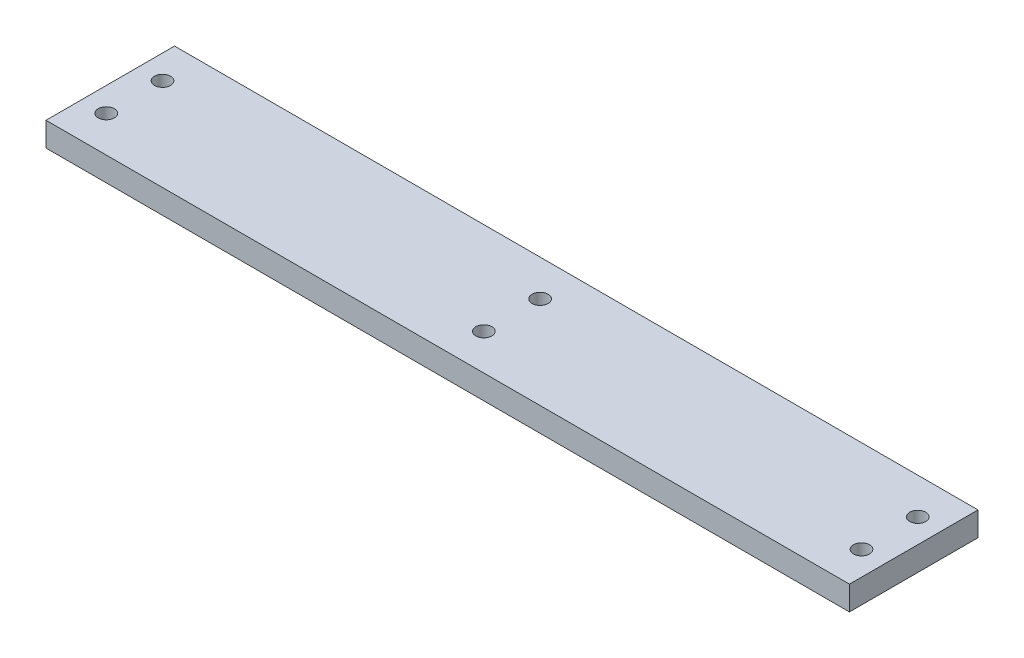
SolidWorks part; units mm, degrees
ref_plane "정면" through (0, 0, 0) normal (0, 0, 1) x (1, 0, 0)
ref_plane "윗면" through (0, 0, 0) normal (0, 1, 0) x (1, 0, 0)
ref_plane "우측면" through (0, 0, 0) normal (1, 0, 0) x (0, 0, -1)
sketch "스케치1" plane through (0, 0, 0) normal (0, 1, 0) x (1, 0, 0)
  line L1 (-50, -8) -> (50, -8)
  line L2 (-50, -8) -> (-50, 8)
  line L3 (-50, 8) -> (50, 8)
  line L4 (50, -8) -> (50, 8)
  line L5 (-50, -8) -> (50, 8) construction
  line L6 (-50, 8) -> (50, -8) construction
  point P0 (0, 0)
  dimension "D1" = 16
  dimension "D2" = 100
extrude "보스-돌출1" add sketch "스케치1" along normal blind 3
sketch "스케치2" plane through (0, 3, 0) normal (0, 1, 0) x (1, 0, 0)
  line L0 (-52.7608, 0) -> (58.8086, 0) construction
  line L1 (0, 14.085) -> (0, -13.5662) construction
  line L2 (50, -8) -> (50, 8) construction
  line L3 (50, 8) -> (-50, 8) construction
  circle A0 centre (47, 3.5) radius 1
  circle A1 centre (0, 3.5) radius 1
  circle A2 centre (-47, 3.5) radius 1
  circle A11 centre (47, -3.5) radius 1
  circle A14 centre (0, -3.5) radius 1
  circle A16 centre (-47, -3.5) radius 1
  point P0 (0, 0)
  point P5 (0, 8)
  point P6 (50, 0)
extrude "컷-돌출1" cut sketch "스케치2" against normal blind 3
